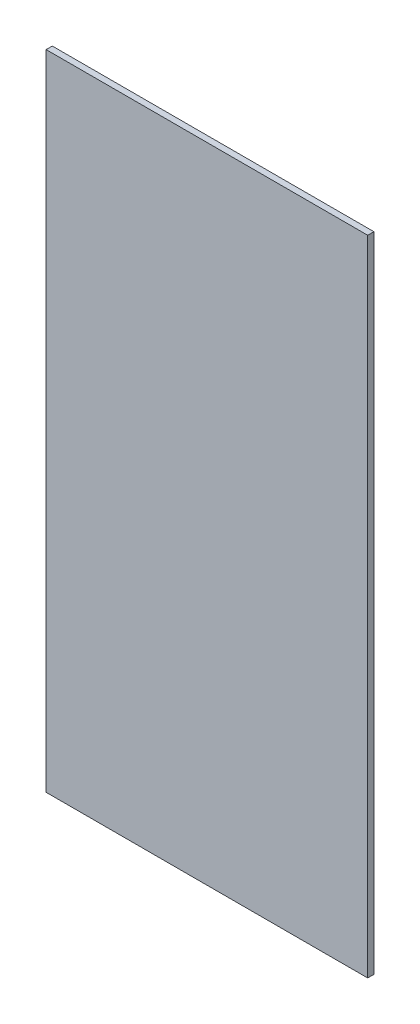
SolidWorks part; units mm, degrees
ref_plane "Front Plane" through (0, 0, 0) normal (0, 0, 1) x (1, 0, 0)
ref_plane "Top Plane" through (0, 0, 0) normal (0, 1, 0) x (1, 0, 0)
ref_plane "Right Plane" through (0, 0, 0) normal (1, 0, 0) x (0, 0, -1)
sketch "Sketch1" plane through (0, 0, 0) normal (0, 0, 1) x (1, 0, 0)
  line L0 (0, 165.1) -> (0, -165.1) construction
  line L1 (-82.55, 165.1) -> (82.55, 165.1)
  line L2 (-82.55, 165.1) -> (-82.55, -165.1)
  line L3 (-82.55, -165.1) -> (82.55, -165.1)
  line L4 (82.55, 165.1) -> (82.55, -165.1)
  point P6 (0, 0)
  dimension "D1" = 165.1
  dimension "D2" = 330.2
extrude "Boss-Extrude1" add sketch "Sketch1" along normal blind 3.175
equation "\"Height\"= 12in"
equation "\"Depth\"= 7in"
equation "\"WallThickness\"= 0.125in"
equation "\"FloorThickness\"= 0.25in"
equation "\"D1@Boss-Extrude1\"=\"WallThickness\""
